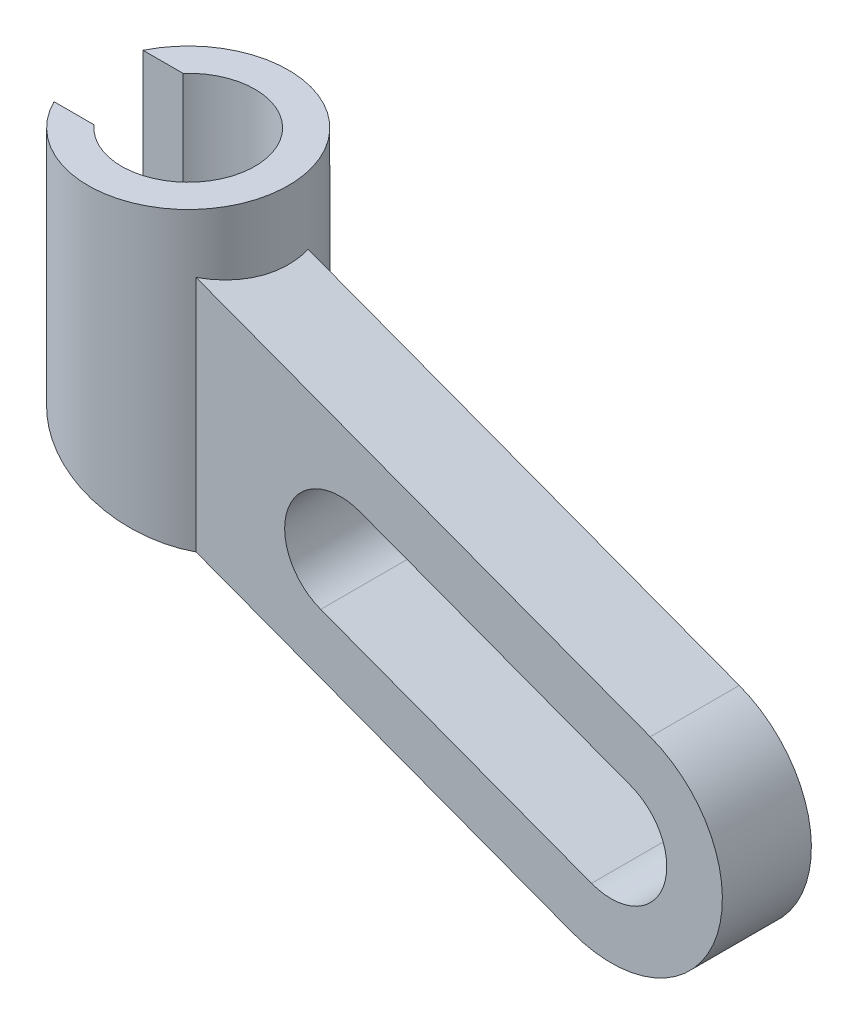
SolidWorks part; units mm, degrees
ref_plane "Спереди" through (0, 0, 0) normal (0, 0, 1) x (1, 0, 0)
ref_plane "Сверху" through (0, 0, 0) normal (0, 1, 0) x (1, 0, 0)
ref_plane "Справа" through (0, 0, 0) normal (1, 0, 0) x (0, 0, -1)
sketch "Эскиз1" plane through (0, 0, 0) normal (0, 0, 1) x (1, 0, 0)
  line L0 (0, 0) -> (0, 7.93) construction
  line L1 (8.9518, 7.2351) -> (21.1202, 2.6599)
  line L2 (21.125, 2.6728) -> (22.875, 7.3272) construction
  line L3 (22.8798, 7.3401) -> (10.7115, 11.9152)
  line L4 (10.7115, 11.9152) -> (8.9518, 7.2351) construction
  line L5 (23.7597, 9.6801) -> (0, 18.6135)
  line L6 (0, 18.6135) -> (0, 7.93)
  line L7 (20.2403, 0.3199) -> (0, 7.93)
  line L8 (0, 0) -> (47.6468, 0) construction
  arc A0 (21.1202, 2.6599) -> (22.8798, 7.3401) centre (22, 5) ccw
  arc A1 (20.2403, 0.3199) -> (23.7597, 9.6801) centre (22, 5) ccw
  arc A2 (10.7115, 11.9152) -> (8.9518, 7.2351) centre (9.8317, 9.5751) ccw
  dimension "D1" = 5
  dimension "D2" = 10
  dimension "D5" = 18
  dimension "D3" = 27
  dimension "D4" = 7.93
extrude "Бобышка-Вытянуть1" add sketch "Эскиз1" along normal blind 3 and the other way blind 1
sketch "Эскиз2" plane through (0, 0, 0) normal (0, 1, 0) x (1, 0, 0)
  circle A0 centre (0, 0) radius 4.5
  circle A1 centre (0, 0) radius 3
  dimension "D1" = 6
  dimension "D2" = 9
extrude "Бобышка-Вытянуть2" add sketch "Эскиз2" along normal blind 20
sketch "Эскиз3" plane through (0, 0, 0) normal (0, -1, 0) x (-1, 0, 0)
  circle A0 centre (0, 0) radius 3
extrude "Вырез-Вытянуть1" cut sketch "Эскиз3" against normal through all
sketch "Эскиз4" plane through (0, 0, 0) normal (0, -1, 0) x (1, 0, 0)
  circle A0 centre (0, 0) radius 9.774
extrude "Вырез-Вытянуть2" cut sketch "Эскиз4" against normal up to surface (7.93 mm away)
sketch "Эскиз5" plane through (0, 0, 0) normal (0, 1, 0) x (1, 0, 0)
  line L0 (0, 0) -> (-7.8806, 0) construction
  line L2 (-14.8214, -2) -> (-0.9399, -2)
  line L3 (-14.8214, -2) -> (-14.8214, 2)
  line L4 (-14.8214, 2) -> (-0.9399, 2)
  line L5 (-0.9399, -2) -> (-0.9399, 2)
  line L6 (-14.8214, -2) -> (-0.9399, 2) construction
  line L7 (-14.8214, 2) -> (-0.9399, -2) construction
  dimension "D1" = 4
extrude "Вырез-Вытянуть4" cut sketch "Эскиз5" along normal through all
